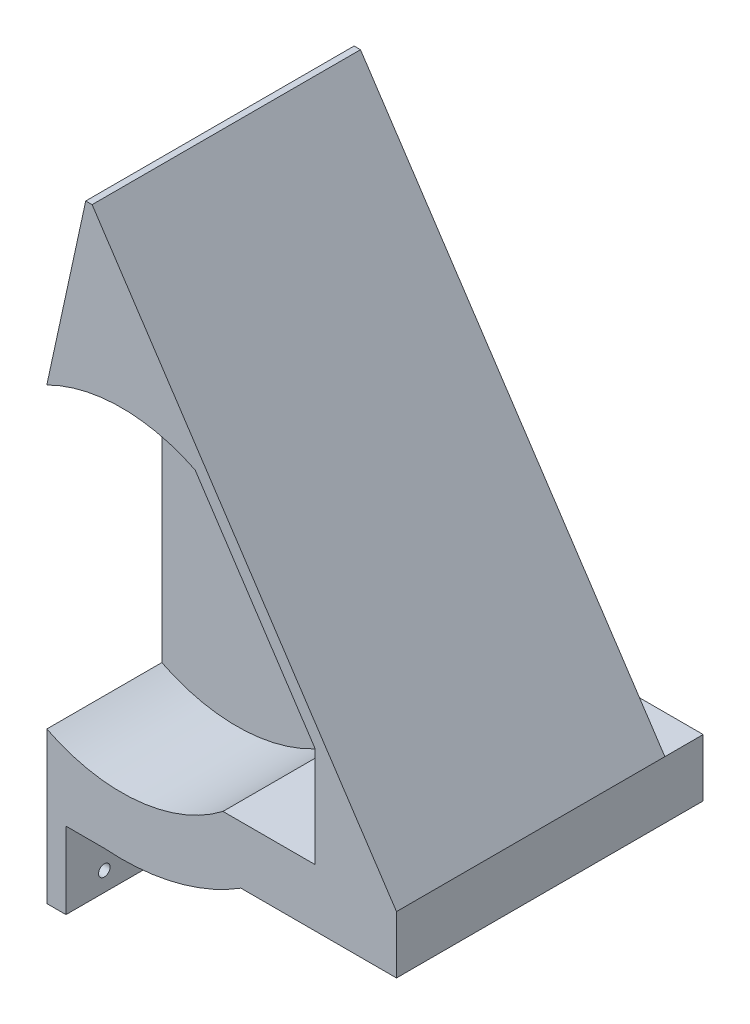
SolidWorks part; units mm, degrees
ref_plane "前视基准面" through (0, 0, 0) normal (0, 0, 1) x (1, 0, 0)
ref_plane "上视基准面" through (0, 0, 0) normal (0, 1, 0) x (1, 0, 0)
ref_plane "右视基准面" through (0, 0, 0) normal (1, 0, 0) x (0, 0, -1)
sketch "草图1" plane through (0, 0, 0) normal (1, 0, 0) x (0, 0, -1)
  line L0 (135, 0) -> (135, -170) construction
  line L1 (0, 0) -> (270, 0)
  line L2 (0, 0) -> (0, -100.2828)
  line L4 (270, 0) -> (270, -100.2828)
  line L5 (38.49, -136.6392) -> (62.3511, -70.3586) construction
  line L6 (21.17, -130.404) -> (127.5448, -168.6989) construction
  line L7 (142.4552, -168.6989) -> (248.83, -130.404) construction
  line L8 (58.2053, -81.8746) -> (-5.8219, -81.8746) construction
  line L9 (58.2053, -81.8746) -> (5.8219, -118.6911) construction
  line L10 (127.5448, -168.6989) -> (21.17, -130.404)
  line L11 (142.4552, -168.6989) -> (248.83, -130.404)
  line L12 (105.5031, -160.7639) -> (135, -78.8281) construction
  line L13 (135, -78.8281) -> (164.4969, -160.7639) construction
  arc A0 (0, -100.2828) -> (21.17, -130.404) centre (32.0136, -100.2828) ccw
  arc A1 (127.5448, -168.6989) -> (142.4552, -168.6989) centre (135, -147.9899) ccw
  arc A2 (270, -100.2828) -> (248.83, -130.404) centre (237.9864, -100.2828) cw
  dimension "D2" = 44.0202
  dimension "D3" = 170
  dimension "D1" = 270
  dimension "D4" = 32.0136
  dimension "D5" = 109.799
  dimension "D6" = 109.799
extrude "凸台-拉伸1" add sketch "草图1" along normal blind 30
sketch "草图2" plane through (30, 0, 0) normal (1, 0, 0) x (0, 0, -1)
  line L0 (135, 0) -> (135, -170) construction
  line L1 (270, 0) -> (0, 0) construction
  line L2 (135, -14.9009) -> (165, -14.9009) construction
  line L3 (165, 0) -> (165, -160.5828)
  line L4 (105, 0) -> (105, -160.5828)
  line L8 (0, 0) -> (0, -100.2828)
  line L9 (21.17, -130.404) -> (127.5448, -168.6989)
  line L10 (142.4552, -168.6989) -> (248.83, -130.404)
  line L11 (270, -100.2828) -> (270, 0)
  line L12 (270, 0) -> (0, 0)
  line L13 (0, 0) -> (0, -100.2828)
  line L14 (21.17, -130.404) -> (127.5448, -168.6989)
  line L15 (142.4552, -168.6989) -> (248.83, -130.404)
  line L16 (270, -100.2828) -> (270, 0)
  line L17 (270, 0) -> (0, 0)
  arc A0 (127.5448, -168.6989) -> (142.4552, -168.6989) centre (135, -147.9899) ccw construction
  arc A4 (0, -100.2828) -> (21.17, -130.404) centre (32.0136, -100.2828) ccw
  arc A5 (127.5448, -168.6989) -> (142.4552, -168.6989) centre (135, -147.9899) ccw
  arc A6 (248.83, -130.404) -> (270, -100.2828) centre (237.9864, -100.2828) ccw
  arc A7 (0, -100.2828) -> (21.17, -130.404) centre (32.0136, -100.2828) ccw
  arc A8 (127.5448, -168.6989) -> (142.4552, -168.6989) centre (135, -147.9899) ccw
  arc A9 (248.83, -130.404) -> (270, -100.2828) centre (237.9864, -100.2828) ccw
  line M12 (0, 0) -> (0, -100.2828)
  arc M13 (0, -100.2828) -> (21.17, -130.404) centre (32.0136, -100.2828) ccw
  line M14 (21.17, -130.404) -> (127.5448, -168.6989)
  line M16 (142.4552, -168.6989) -> (248.83, -130.404)
  arc M17 (248.83, -130.404) -> (270, -100.2828) centre (237.9864, -100.2828) ccw
  line M18 (270, -100.2828) -> (270, 0)
  line M19 (270, 0) -> (0, 0)
  dimension "D1" = 30
  dimension "D2" = 0
extrude "凸台-拉伸2" add sketch "草图2" along normal blind 210 contours L4 M19 M12 M13 M14 | L3 M19 M16 M17 M18
sketch "草图6" plane through (0, 0, -105) normal (0, 0, -1) x (-1, 0, 0)
  line L0 (-71.1167, 0) -> (-71.1167, -409.9146) construction
  line L8 (-30, -160.5828) -> (-30, 0)
  line L9 (-30, 0) -> (-240, 0)
  line L12 (-240, 0) -> (-240, -160.5828)
  line L13 (-240, -160.5828) -> (-30, -160.5828)
  line L15 (-30, -160.5828) -> (-30, 0)
  line L16 (-30, 0) -> (-240, 0)
  line L19 (-240, 0) -> (-240, -160.5828)
  line L20 (-240, -160.5828) -> (-30, -160.5828)
  dimension "D2" = 41.1167
  dimension "D1" = 0
sketch "草图8" plane through (240, 0, 0) normal (1, 0, 0) x (0, 0, -1)
  line L0 (105, 0) -> (105, -160.5828) construction
  line L1 (105, -60) -> (80, -60)
  line L2 (105, -60) -> (105, 60)
  line L3 (105, 60) -> (80, 60)
  line L4 (80, -60) -> (80, 60)
  line L5 (105, -60) -> (80, 60) construction
  line L6 (105, 60) -> (80, -60) construction
  line L7 (135, 0) -> (135, -208.0575) construction
  line L8 (165, 0) -> (105, 0) construction
  line L9 (105, 0) -> (0, 0) construction
  line L10 (165, 60) -> (190, -60) construction
  line L11 (165, -60) -> (190, 60) construction
  line L12 (190, -60) -> (190, 60)
  line L13 (165, 60) -> (190, 60)
  line L14 (165, -60) -> (165, 60)
  line L15 (165, -60) -> (190, -60)
  point P4 (92.5, 0)
  point P17 (177.5, 0)
  dimension "D1" = 25
  dimension "D2" = 60
  dimension "D3" = 60
extrude "凸台-拉伸5" add sketch "草图8" along normal blind 70
sketch "草图9" plane through (240, 0, 0) normal (-1, 0, 0) x (0, 0, 1)
  line L4 (-105, 60) -> (-105, 0)
  line L5 (-105, 0) -> (-80, 0)
  line L6 (-80, 0) -> (-80, 60)
  line L7 (-80, 60) -> (-105, 60)
  line L8 (-105, 60) -> (-105, 0)
  line L9 (-105, 0) -> (-80, 0)
  line L10 (-80, 0) -> (-80, 60)
  line L11 (-80, 60) -> (-105, 60)
  line L12 (-190, 0) -> (-165, 0)
  line L13 (-165, 0) -> (-165, 60)
  line L14 (-165, 60) -> (-190, 60)
  line L15 (-190, 60) -> (-190, 0)
  line L16 (-190, 0) -> (-165, 0)
  line L17 (-165, 0) -> (-165, 60)
  line L18 (-165, 60) -> (-190, 60)
  line L19 (-190, 60) -> (-190, 0)
  dimension "D1" = 0
  dimension "D2" = 0
extrude "凸台-拉伸6" add sketch "草图9" along normal blind 60
sketch "草图10" plane through (0, 0, -80) normal (0, 0, 1) x (1, 0, 0)
  line L0 (240, 0) -> (240, 31.0013) construction
  line L2 (180, 30) -> (270, 30) construction
  line L3 (180, 0) -> (180, 60) construction
  circle A0 centre (270, 30) radius 7.5
  dimension "D2" = 15
  dimension "D1" = 30
extrude "切除-拉伸3" cut sketch "草图10" against normal through all
sketch "草图11" plane through (0, 0, -105) normal (0, 0, -1) x (-1, 0, 0)
  line L0 (0, 0) -> (0, 80.2418) construction
  line L1 (-240, -160.5828) -> (-124.1295, -160.5828) construction
  line L2 (-124.1295, -160.5828) -> (-108.2032, -160.5828) construction
  line L3 (-30, 0) -> (-30, -40) construction
  line L4 (-30, -40) -> (-30, -160.5828)
  line L5 (-30, -160.5828) -> (-108.2032, -160.5828)
  circle A0 centre (-270, 30) radius 240 construction
  arc A1 (-108.2032, -160.5828) -> (-30, -40) centre (-270, 30) ccw
  circle A2 centre (-270, 30) radius 250 construction
  dimension "D1" = 480
  dimension "D2" = 10
extrude "凸台-拉伸7" add sketch "草图11" along normal blind 60
sketch "草图12" plane through (0, 0, -165) normal (0, 0, 1) x (1, 0, 0)
  line L0 (30, 0) -> (240, 0) construction
  line L1 (70, -45) -> (70, 0) construction
  line L4 (30, -160.5828) -> (30, 0) construction
  circle A0 centre (70, -45) radius 2.5
  dimension "D3" = 5
  dimension "D4" = 45
  dimension "D1" = 45
  dimension "D2" = 40
extrude "凸台-拉伸8" add sketch "草图12" along normal through all
sketch "草图13" plane through (0, 0, 0) normal (0, 1, 0) x (1, 0, 0)
  line L0 (0, 270) -> (0, 240.5719) construction
  line L1 (0, 270) -> (0, 0) construction
  line L2 (0, 240.5719) -> (0, 192.1942) construction
sketch "草图14" plane through (0, 0, 0) normal (0, 1, 0) x (1, 0, 0)
  line L0 (0, 250) -> (0, 200)
  line L1 (0, 250) -> (125, 250)
  line L2 (0, 200) -> (125, 200)
  line L3 (125, 250) -> (125, 200)
  line L4 (0, 270) -> (0, 0) construction
  line L5 (240, 270) -> (0, 270) construction
  line L6 (0, 135) -> (52.375, 135) construction
  line L7 (125, 20) -> (125, 70)
  line L8 (0, 70) -> (125, 70)
  line L9 (0, 20) -> (125, 20)
  line L10 (0, 20) -> (0, 70)
  dimension "D1" = 20
  dimension "D2" = 50
  dimension "D3" = 125
extrude "凸台-拉伸9" add sketch "草图14" along normal blind 120
sketch "草图15" plane through (0, 0, -20) normal (0, 0, 1) x (1, 0, 0)
  line L0 (0, 120) -> (0, 0) construction
  line L1 (0, 70) -> (70, 70)
  line L2 (0, 70) -> (0, 0)
  line L3 (0, 0) -> (70, 0)
  line L4 (70, 70) -> (70, 0)
  line L5 (0, 120) -> (125, 120) construction
  dimension "D1" = 70
  dimension "D2" = 70
  dimension "D3" = 50
extrude "切除-拉伸4" cut sketch "草图15" against normal blind 10
sketch "草图16" plane through (0, 0, -30) normal (0, 0, 1) x (1, 0, 0)
  line L0 (0, 35) -> (70, 35) construction
  line L1 (0, 70) -> (0, 0) construction
  line L2 (70, 0) -> (70, 70) construction
  line L3 (0, 35) -> (35, 35) construction
  line L4 (35, 70) -> (35, 0) construction
  line L5 (35, 35) -> (35, 15)
  line L6 (70, 70) -> (0, 70) construction
  line L7 (0, 35) -> (35, 35) construction
  line L8 (0, 0) -> (70, 0) construction
  line L9 (35, 35) -> (35, 55) construction
  line L10 (35, 55) -> (5, 55) construction
  line L11 (35, 35) -> (35, 55)
  line L12 (35, 55) -> (5, 55)
  line L13 (5, 55) -> (5, 15)
  line L14 (35, 15) -> (5, 15)
  point P21 (5, 35)
  dimension "D1" = 35
  dimension "D2" = 20
  dimension "D3" = 30
extrude "切除-拉伸5" cut sketch "草图16" against normal blind 20 contours L14 L5 L11 L12 L13
sketch "草图17" plane through (0, 0, -30) normal (0, 0, 1) x (1, 0, 0)
  line L0 (35, 35) -> (19.5, 34.5) construction
  line L1 (35, 55) -> (35, 15) construction
  circle A0 centre (19.5, 34.5) radius 43.4713
extrude "切除-拉伸6" cut sketch "草图17" along normal through all
sketch "草图18" plane through (0, 0, -20) normal (0, 0, 1) x (1, 0, 0)
  line L0 (0, 73.3523) -> (11.8199, 120) construction
  line L1 (0, 73.3523) -> (0, -4.3523) construction
  line L2 (0, 120) -> (125, 120) construction
  line L3 (11.8199, 120) -> (62.5, 43.3973) construction
  line L4 (62.5, 43.3973) -> (91.2115, 0) construction
  line L5 (11.8199, 120) -> (91.2115, 0)
  line L6 (91.2115, 0) -> (87.3179, 0)
  line L7 (70, 0) -> (125, 0) construction
  line L8 (87.3179, 0) -> (10.7417, 115.7446)
  line L9 (10.7417, 115.7446) -> (11.8199, 120)
  arc A0 (44.5899, 70) -> (0, 73.3523) centre (19.5, 34.5) ccw construction
extrude "凸台-拉伸10" add sketch "草图18" along normal blind 20
sketch "草图19" plane through (0, 0, -20) normal (0, 0, 1) x (1, 0, 0)
  line L0 (10.856, 115.5717) -> (11.8199, 120)
  line L1 (10.7417, 115.7446) -> (87.3179, 0) construction
  line L2 (11.8199, 120) -> (10.7417, 115.7446) construction
  line L3 (11.8199, 120) -> (125, 120) construction
  line L4 (11.8199, 120) -> (0, 65.6972)
  line L5 (0, 73.3523) -> (0, -4.3523) construction
  line L6 (0, 65.6972) -> (0, 73.3523)
  line L7 (0, 120) -> (0, 73.3523) construction
  line L8 (0, 73.3523) -> (10.1537, 120)
  line L9 (0, 120) -> (11.8199, 120) construction
  line L10 (10.1537, 120) -> (11.8199, 120)
  line L11 (10.1537, 120) -> (11.8199, 120)
  line M2 (38.6846, 73.509) -> (10.7417, 115.7446)
  line M3 (10.7417, 115.7446) -> (11.8199, 120)
  line M4 (11.8199, 120) -> (0, 120)
  arc M6 (0, 73.3523) -> (38.6846, 73.509) centre (19.5, 34.5) cw
extrude "凸台-拉伸11" add sketch "草图19" along normal blind 20 contours L8 L4 M6 M2 M3 M4
sketch "草图20" plane through (0, 0, -20) normal (0, 0, 1) x (1, 0, 0)
  line L3 (0, 120) -> (0, 73.3523)
  line L4 (0, 73.3523) -> (10.1537, 120)
  line L5 (10.1537, 120) -> (0, 120)
  line L6 (0, 120) -> (0, 73.3523)
  line L7 (0, 73.3523) -> (10.1537, 120)
  line L8 (10.1537, 120) -> (0, 120)
  dimension "D1" = 0
extrude "切除-拉伸7" cut sketch "草图20" against normal through all
sketch "草图22" plane through (0, 0, -20) normal (0, 0, 1) x (1, 0, 0)
  line L0 (44.8997, 70) -> (70, 32.0611)
  line L7 (70, 32.0611) -> (91.2115, 0)
  line L8 (91.2115, 0) -> (125, 0)
  line L9 (125, 0) -> (125, 120)
  line L10 (125, 120) -> (11.8199, 120)
  line L11 (11.8199, 120) -> (44.8997, 70)
  line L12 (44.8997, 70) -> (70, 70)
  line L13 (70, 70) -> (70, 32.0611)
  line L14 (70, 32.0611) -> (91.2115, 0)
  line L15 (91.2115, 0) -> (125, 0)
  line L16 (125, 0) -> (125, 120)
  line L17 (125, 120) -> (11.8199, 120)
  line L18 (11.8199, 120) -> (44.8997, 70)
  dimension "D1" = 0
extrude "切除-拉伸8" cut sketch "草图22" against normal through all
sketch "草图23" plane through (0, 0, 0) normal (0, 0, 1) x (1, 0, 0)
  line L0 (87.3179, 0) -> (91.2115, 0)
  line L10 (0, -4.3523) -> (0, -100.2828)
  line L11 (0, -100.2828) -> (240, -100.2828)
  line L12 (240, -100.2828) -> (240, 0)
  line L13 (240, 0) -> (91.2115, 0)
  line L14 (91.2115, 0) -> (11.8199, 120)
  line L15 (11.8199, 120) -> (10.1537, 120)
  line L16 (10.1537, 120) -> (0, 73.3523)
  line L17 (1.8573, 74.2302) -> (10.856, 115.5717)
  line L18 (10.856, 115.5717) -> (87.3179, 0)
  line L19 (87.3179, 0) -> (45.9481, 0)
  line L20 (0, -4.3523) -> (0, -100.2828)
  line L21 (0, -100.2828) -> (240, -100.2828)
  line L22 (240, -100.2828) -> (240, 0)
  line L23 (240, 0) -> (91.2115, 0)
  line L24 (91.2115, 0) -> (11.8199, 120)
  line L25 (11.8199, 120) -> (10.1537, 120)
  line L26 (10.1537, 120) -> (0, 73.3523)
  line L27 (1.8573, 74.2302) -> (10.856, 115.5717)
  line L28 (10.856, 115.5717) -> (87.3179, 0)
  line L29 (87.3179, 0) -> (45.9481, 0)
  arc A2 (0, -4.3523) -> (45.9481, 0) centre (19.5, 34.5) ccw
  arc A3 (1.8573, 74.2302) -> (0, 73.3523) centre (19.5, 34.5) ccw
  arc A4 (0, -4.3523) -> (45.9481, 0) centre (19.5, 34.5) ccw
  arc A5 (1.8573, 74.2302) -> (0, 73.3523) centre (19.5, 34.5) ccw
  line M18 (91.2115, 0) -> (11.8199, 120)
  line M19 (11.8199, 120) -> (10.1537, 120)
  line M20 (10.1537, 120) -> (0, 73.3523)
  arc M21 (0, 73.3523) -> (1.8573, 74.2302) centre (19.5, 34.5) cw
  line M22 (1.8573, 74.2302) -> (10.856, 115.5717)
  line M23 (10.856, 115.5717) -> (87.3179, 0)
  dimension "D1" = 0
extrude "凸台-拉伸19" add sketch "草图23" against normal up to next contours L0 M23 M18 M19 M20 M21 M22
sketch "草图24" plane through (0, 0, -20) normal (0, 0, 1) x (1, 0, 0)
  line L3 (87.3179, 0) -> (70, 26.1759)
  line L4 (70, 26.1759) -> (70, 0)
  line L5 (70, 0) -> (87.3179, 0)
  line L6 (87.3179, 0) -> (70, 26.1759)
  line L7 (70, 26.1759) -> (70, 0)
  line L8 (70, 0) -> (87.3179, 0)
  dimension "D1" = 0
extrude "凸台-拉伸20" add sketch "草图24" along normal up to vertex (20 mm away)
sketch "草图25" plane through (0, 0, -20) normal (0, 0, 1) x (1, 0, 0)
  line L2 (38.6846, 73.509) -> (10.856, 115.5717)
  line L3 (10.856, 115.5717) -> (1.8573, 74.2302)
  line L4 (38.6846, 73.509) -> (10.856, 115.5717)
  line L5 (10.856, 115.5717) -> (1.8573, 74.2302)
  arc A1 (38.6846, 73.509) -> (1.8573, 74.2302) centre (19.5, 34.5) ccw
  arc A2 (38.6846, 73.509) -> (1.8573, 74.2302) centre (19.5, 34.5) ccw
  dimension "D1" = 0
extrude "凸台-拉伸21" add sketch "草图25" along normal blind 20
sketch "草图26" plane through (0, 0, -250) normal (0, 0, -1) x (-1, 0, 0)
  line L10 (-70, 26.1759) -> (-38.6846, 73.509)
  line L11 (-70, 0) -> (-70, 26.1759)
  line L12 (-45.9481, 0) -> (-70, 0)
  line L13 (0, -100.2828) -> (0, -4.3523)
  line L14 (-240, -100.2828) -> (0, -100.2828)
  line L15 (-240, 0) -> (-240, -100.2828)
  line L16 (-91.2115, 0) -> (-240, 0)
  line L17 (-11.8199, 120) -> (-91.2115, 0)
  line L18 (-10.1537, 120) -> (-11.8199, 120)
  line L19 (0, 73.3523) -> (-10.1537, 120)
  line L20 (-70, 26.1759) -> (-38.6846, 73.509)
  line L21 (-70, 0) -> (-70, 26.1759)
  line L22 (-45.9481, 0) -> (-70, 0)
  line L23 (0, -100.2828) -> (0, -4.3523)
  line L24 (-240, -100.2828) -> (0, -100.2828)
  line L25 (-240, 0) -> (-240, -100.2828)
  line L26 (-91.2115, 0) -> (-240, 0)
  line L27 (-11.8199, 120) -> (-91.2115, 0)
  line L28 (-10.1537, 120) -> (-11.8199, 120)
  line L29 (0, 73.3523) -> (-10.1537, 120)
  arc A2 (0, 73.3523) -> (-38.6846, 73.509) centre (-19.5, 34.5) ccw
  arc A3 (-45.9481, 0) -> (0, -4.3523) centre (-19.5, 34.5) ccw
  arc A4 (0, 73.3523) -> (-38.6846, 73.509) centre (-19.5, 34.5) ccw
  arc A5 (-45.9481, 0) -> (0, -4.3523) centre (-19.5, 34.5) ccw
  dimension "D1" = 0
extrude "凸台-拉伸22" add sketch "草图26" along normal blind 20
sketch "草图27" plane through (0, 0, -270) normal (0, 0, -1) x (-1, 0, 0)
  line L4 (-38.6846, 73.509) -> (-70, 26.1759)
  line L5 (0, -4.3523) -> (0, 73.3523)
  line L6 (-70, 0) -> (-45.9481, 0)
  line L7 (-70, 26.1759) -> (-70, 0)
  line L8 (-38.6846, 73.509) -> (-70, 26.1759)
  line L9 (0, -4.3523) -> (0, 73.3523)
  line L10 (-70, 0) -> (-45.9481, 0)
  line L11 (-70, 26.1759) -> (-70, 0)
  arc A2 (0, 73.3523) -> (-38.6846, 73.509) centre (-19.5, 34.5) ccw
  arc A3 (-45.9481, 0) -> (0, -4.3523) centre (-19.5, 34.5) ccw
  arc A4 (0, 73.3523) -> (-38.6846, 73.509) centre (-19.5, 34.5) ccw
  arc A5 (-45.9481, 0) -> (0, -4.3523) centre (-19.5, 34.5) ccw
  dimension "D1" = 0
extrude "切除-拉伸9" cut sketch "草图27" against normal blind 30
sketch "草图29" plane through (0, 0, -70) normal (0, 0, -1) x (-1, 0, 0)
  line L0 (-5, 55) -> (-35, 15) construction
  line L1 (-5, 15) -> (-35, 55) construction
  line L4 (-35, 15) -> (-5, 15)
  line L5 (-35, 55) -> (-35, 15)
  line L6 (-5, 55) -> (-35, 55)
  line L7 (-5, 15) -> (-5, 55)
  line L8 (-35, 15) -> (-5, 15) construction
  line L9 (-35, 55) -> (-35, 15) construction
  line L10 (-5, 55) -> (-35, 55) construction
  line L11 (-5, 15) -> (-5, 55) construction
  circle A0 centre (-20, 35) radius 15
  dimension "D2" = 30
  dimension "D1" = 0
extrude "切除-拉伸11" cut sketch "草图29" against normal through all both and the other way through all
sketch "草图30" plane through (30, 0, 0) normal (1, 0, 0) x (0, 0, -1)
  line L3 (142.4552, -168.6989) -> (165, -160.5828)
  line L4 (165, -160.5828) -> (105, -160.5828)
  line L5 (105, -160.5828) -> (127.5448, -168.6989)
  line L6 (142.4552, -168.6989) -> (165, -160.5828)
  line L7 (165, -160.5828) -> (105, -160.5828)
  line L8 (105, -160.5828) -> (127.5448, -168.6989)
  arc A1 (127.5448, -168.6989) -> (142.4552, -168.6989) centre (135, -147.9899) ccw
  arc A2 (127.5448, -168.6989) -> (142.4552, -168.6989) centre (135, -147.9899) ccw
  dimension "D1" = 0
extrude "凸台-拉伸23" add sketch "草图30" along normal up to vertex (78.2032 mm away)
sketch "草图33" plane through (0, 0, -240) normal (0, 0, -1) x (-1, 0, 0)
  line L0 (-35, 15) -> (-5, 15) construction
  line L1 (-35, 55) -> (-35, 15) construction
  line L2 (-35, 55) -> (-5, 55) construction
  line L3 (-5, 55) -> (-5, 15) construction
  line L4 (-35, 15) -> (-5, 15)
  line L5 (-35, 55) -> (-35, 15)
  line L6 (-35, 55) -> (-5, 55)
  line L7 (-5, 55) -> (-5, 15)
extrude "切除-拉伸14" cut sketch "草图33" against normal blind 20
sketch "草图34" plane through (0, 0, -200) normal (0, 0, 1) x (1, 0, 0)
  line L0 (20, 50) -> (20, 2.4606) construction
  line L1 (11, 0) -> (11, 35.3006)
  line L2 (11, 0) -> (29, 0)
  line L3 (11, 35.3006) -> (29, 35.3006)
  line L4 (29, 0) -> (29, 35.3006)
  line L5 (11, 0) -> (29, 35.3006) construction
  line L6 (11, 35.3006) -> (29, 0) construction
  line L7 (0, 0) -> (91.2115, 0) construction
  arc A0 (35, 35) -> (5, 35) centre (20, 35) ccw construction
  point P7 (20, 17.6503)
  dimension "D1" = 18
extrude "切除-拉伸15" cut sketch "草图34" against normal blind 10
sketch "草图35" plane through (0, 0, -70) normal (0, 0, -1) x (-1, 0, 0)
  line L3 (-11, 0) -> (-11, 23)
  line L4 (-29, 0) -> (-11, 0)
  line L5 (-29, 23) -> (-29, 0)
  line L6 (-11, 0) -> (-11, 23)
  line L7 (-29, 0) -> (-11, 0)
  line L8 (-29, 23) -> (-29, 0)
  arc A1 (-29, 23) -> (-11, 23) centre (-20, 35) ccw
  arc A2 (-29, 23) -> (-11, 23) centre (-20, 35) ccw
  dimension "D1" = 0
extrude "切除-拉伸16" cut sketch "草图35" against normal blind 10
sketch "草图36" plane through (0, 0, 0) normal (-1, 0, 0) x (0, 0, 1)
  line L0 (-235.6917, -100.008) -> (-211.6417, -100.008) construction
  line L1 (-135, -147.9899) -> (-135, -104.794) construction
  line L2 (-34.3083, -100.008) -> (-58.3583, -100.008) construction
  circle A0 centre (-235.6917, -100.008) radius 15.9
  circle A1 centre (-34.3083, -100.008) radius 15.9
  ellipse E0 centre (-235.6917, -100.008) end of major axis (-211.6417, -100.008) minor radius 15.9
  ellipse E1 centre (-34.3083, -100.008) end of major axis (-58.3583, -100.008) minor radius 15.9
  dimension "D2" = 31.8
  dimension "D1" = 24.05
extrude "切除-拉伸17" cut sketch "草图36" against normal blind 4 contours A0 E0 | A0 | A0 E0 | E1 A1 | A1 | E1 A1
sketch "草图37" plane through (0, 0, 0) normal (0, 1, 0) x (1, 0, 0)
  line L0 (108.2032, 135) -> (337.5794, 135) construction
  line L1 (240, 80) -> (91.2115, 80)
  line L2 (240, 80) -> (240, 0)
  line L3 (240, 0) -> (91.2115, 0)
  line L4 (91.2115, 80) -> (91.2115, 0)
  line L5 (108.2032, 165) -> (108.2032, 105) construction
  line L6 (91.2115, 190) -> (91.2115, 270)
  line L7 (240, 270) -> (91.2115, 270)
  line L8 (240, 190) -> (240, 270)
  line L9 (240, 190) -> (91.2115, 190)
extrude "切除-拉伸18" cut sketch "草图37" against normal through all
sketch "草图38" plane through (0, 0, 0) normal (0, 0, 1) x (1, 0, 0)
  line L1 (70, -15) -> (76.2115, -15)
  line L2 (76.2115, -85.2828) -> (76.2115, -15)
  line L3 (15, -85.2828) -> (76.2115, -85.2828)
  line L4 (15, -23.7978) -> (15, -85.2828)
  line L5 (70, -15) -> (50.623, -15)
  line L6 (76.2115, -15) -> (91.2115, -15)
  line L7 (91.2115, -100.2828) -> (91.2115, 0) construction
  line L8 (91.2115, -15) -> (91.2115, -100.2828)
  line L9 (91.2115, -100.2828) -> (0, -100.2828) construction
  line L10 (91.2115, -100.2828) -> (15, -100.2828)
  line L11 (15, -100.2828) -> (15, -85.2828)
  line L12 (91.2115, -15) -> (91.2115, -100.2828)
  line L14 (91.2115, -151.5828) -> (91.2115, 0) construction
  line L15 (91.2115, -151.5828) -> (91.2115, 0)
  line L17 (91.2115, -151.5828) -> (15, -151.5828)
  line L18 (91.2115, -151.5828) -> (91.2115, -100.2828)
  line L19 (91.2115, -100.2828) -> (15, -100.2828)
  line L20 (15, -151.5828) -> (15, -100.2828)
  arc A0 (15, -23.7978) -> (50.623, -15) centre (19.5, 34.5) ccw
  line M12 (0, -100.2828) -> (91.2115, -100.2828)
  line M13 (91.2115, -100.2828) -> (91.2115, 0)
extrude "切除-拉伸20" cut sketch "草图38" against normal blind 80 contours L20 L17 L15 M12 | L11 L6 L2 L3 M12 M13 | A0 L4 L3 L2 L1 L5
sketch "草图39" plane through (0, 0, -270) normal (0, 0, -1) x (-1, 0, 0)
  line L10 (-180, 60) -> (-310, 60)
  line L11 (-180, 0) -> (-180, 60)
  line L12 (-91.2115, 0) -> (-180, 0)
  line L13 (-91.2115, -15) -> (-91.2115, 0)
  line L14 (-50.623, -15) -> (-91.2115, -15)
  line L15 (-15, -151.5828) -> (-15, -23.7978)
  line L16 (-240, -151.5828) -> (-15, -151.5828)
  line L17 (-240, -60) -> (-240, -151.5828)
  line L18 (-310, -60) -> (-240, -60)
  line L19 (-310, 60) -> (-310, -60)
  line L20 (-180, 60) -> (-310, 60)
  line L21 (-180, 0) -> (-180, 60)
  line L22 (-91.2115, 0) -> (-180, 0)
  line L23 (-91.2115, -15) -> (-91.2115, 0)
  line L24 (-50.623, -15) -> (-91.2115, -15)
  line L25 (-15, -151.5828) -> (-15, -23.7978)
  line L26 (-240, -151.5828) -> (-15, -151.5828)
  line L27 (-240, -60) -> (-240, -151.5828)
  line L28 (-310, -60) -> (-240, -60)
  line L29 (-310, 60) -> (-310, -60)
  arc A1 (-50.623, -15) -> (-15, -23.7978) centre (-19.5, 34.5) ccw
  arc A2 (-50.623, -15) -> (-15, -23.7978) centre (-19.5, 34.5) ccw
  dimension "D1" = 0
extrude "切除-拉伸21" cut sketch "草图39" against normal blind 81
sketch "草图40" plane through (0, 0, -80) normal (0, 0, 1) x (1, 0, 0)
  line L0 (98.1638, -151.5828) -> (30, -151.5828) construction
  line L1 (240, -151.5828) -> (15, -151.5828) construction
  line L2 (30, -151.5828) -> (30, -40) construction
  line L3 (74.6558, -141.5828) -> (40, -141.5828)
  line L4 (40, -141.5828) -> (40, -91.2436)
  arc A1 (30, -40) -> (108.2032, -160.5828) centre (270, 30) ccw construction
  arc A2 (30, -40) -> (98.1638, -151.5828) centre (270, 30) ccw construction
  arc A3 (40, -91.2436) -> (74.6558, -141.5828) centre (270, 30) ccw
  dimension "D1" = 10
extrude "切除-拉伸22" cut sketch "草图40" against normal through all
sketch "草图41" plane through (0, 0, 0) normal (0, 1, 0) x (1, 0, 0)
  line L0 (29, 60) -> (11, 60) construction
  line L1 (29, 60) -> (11, 60)
  line L2 (29, 60) -> (29, 70) construction
  line L3 (29, 60) -> (29, 70)
  line L4 (11, 60) -> (11, 70) construction
  line L5 (11, 60) -> (11, 70)
  line L6 (11, 70) -> (29, 70)
  line L7 (0, 135) -> (128.1299, 135) construction
  line L8 (0, 200) -> (0, 70) construction
  line L9 (11, 200) -> (29, 200)
  line L10 (11, 210) -> (11, 200)
  line L11 (29, 210) -> (29, 200)
  line L12 (29, 210) -> (11, 210)
extrude "切除-拉伸23" cut sketch "草图41" against normal blind 60
sketch "草图44" plane through (0, 60, 0) normal (0, 1, 0) x (1, 0, 0)
  line L0 (310, 80) -> (180, 80) construction
  line L1 (310, 189) -> (260, 189)
  line L2 (310, 189) -> (310, 80)
  line L3 (310, 80) -> (260, 80)
  line L4 (260, 189) -> (260, 80)
  dimension "D1" = 50
extrude "凸台-拉伸26" add sketch "草图44" along normal blind 15
sketch "草图45" plane through (0, -60, 0) normal (0, -1, 0) x (1, 0, 0)
  line L0 (310, -189) -> (240, -189) construction
  line L1 (310, -80) -> (260, -80)
  line L2 (310, -80) -> (310, -189)
  line L3 (310, -189) -> (260, -189)
  line L4 (260, -80) -> (260, -189)
  dimension "D1" = 50
extrude "凸台-拉伸27" add sketch "草图45" along normal blind 15
sketch "草图46" plane through (240, 0, 0) normal (1, 0, 0) x (0, 0, -1)
  line L0 (80, -151.5828) -> (105, -160.5828) construction
  line L1 (80, -151.5828) -> (105, -160.5828)
  line L2 (165, -160.5828) -> (190, -151.5828) construction
  line L3 (165, -160.5828) -> (189, -151.9428)
  line L4 (105, -160.5828) -> (165, -160.5828)
  line L5 (189, -60) -> (189, -151.5828) construction
  line L7 (80, -151.5828) -> (80, -130.5828)
  line L8 (80, -130.5828) -> (189, -130.5828)
  line L10 (189, -130.5828) -> (189, -151.9428)
  dimension "D2" = 30
extrude "凸台-拉伸28" add sketch "草图46" along normal blind 15
sketch "草图47" plane through (0, 0, -189) normal (0, 0, -1) x (-1, 0, 0)
  line L1 (-40, -91.2436) -> (-25, -91.2436)
  line L2 (-40, -91.2436) -> (-40, -141.5828)
  line L3 (-40, -141.5828) -> (-25, -141.5828)
  line L4 (-25, -91.2436) -> (-25, -141.5828)
  arc A0 (-74.6558, -141.5828) -> (-40, -91.2436) centre (-270, 30) ccw construction
  arc A1 (-74.6558, -141.5828) -> (-40, -91.2436) centre (-270, 30) ccw construction
  arc A2 (-108.2032, -160.5828) -> (-30, -40) centre (-270, 30) ccw construction
  arc A3 (-108.2032, -160.5828) -> (-30, -40) centre (-270, 30) ccw construction
  dimension "D1" = 15
extrude "切除-拉伸24" cut sketch "草图47" against normal up to surface (109 mm away) up to face at (51.0572, -125.1437, -80)
sketch "草图48" plane through (310, 0, 0) normal (1, 0, 0) x (0, 0, -1)
  line L5 (270, 120) -> (80, 120)
  line L6 (270, 120) -> (270, -151.5828)
  line L8 (80, 120) -> (80, -151.5828)
  line L10 (80, -151.5828) -> (80, -184.4308)
  line L11 (80, -184.4308) -> (270, -184.4308)
  line L12 (270, -151.5828) -> (270, -184.4308)
extrude "切除-拉伸25" cut sketch "草图48" against normal through all
sketch "草图49" plane through (0, 0, 0) normal (-1, 0, 0) x (0, 0, 1)
  line L0 (-70, -23.7978) -> (-60, -23.7978)
  line L8 (-60, -23.7978) -> (-60, -60)
  line L9 (0, -23.7978) -> (-60, -23.7978)
  line L10 (0, -100.2828) -> (0, -23.7978)
  line L11 (-80, -151.5828) -> (-21.17, -130.404)
  line L12 (-80, -23.7978) -> (-80, -151.5828)
  line L13 (-70, -23.7978) -> (-80, -23.7978)
  line L14 (-70, -60) -> (-70, -23.7978)
  line L15 (-60, -60) -> (-70, -60)
  line L17 (0, -23.7978) -> (-60, -23.7978)
  line L18 (0, -100.2828) -> (0, -23.7978)
  line L19 (-80, -151.5828) -> (-21.17, -130.404)
  line L20 (-80, -23.7978) -> (-80, -151.5828)
  line L21 (-70, -23.7978) -> (-80, -23.7978)
  arc A1 (-21.17, -130.404) -> (0, -100.2828) centre (-32.0136, -100.2828) ccw
  arc A2 (-21.17, -130.404) -> (0, -100.2828) centre (-32.0136, -100.2828) ccw
  dimension "D1" = 0
extrude "切除-拉伸26" cut sketch "草图49" against normal blind 15
sketch "草图50" plane through (0, -23.7978, 0) normal (0, -1, 0) x (1, 0, 0)
  line L0 (15, -80) -> (0, -80) construction
  line L1 (0, 0) -> (5, 0)
  line L2 (0, 0) -> (0, -80)
  line L3 (0, -80) -> (5, -80)
  line L4 (5, 0) -> (5, -80)
  dimension "D1" = 5
extrude "凸台-拉伸29" add sketch "草图50" along normal blind 20
sketch "草图51" plane through (5, 0, 0) normal (1, 0, 0) x (0, 0, -1)
  line L0 (80, -33.7978) -> (0, -33.7978) construction
  line L1 (80, -43.7978) -> (80, -23.7978) construction
  line L2 (0, -43.7978) -> (0, -23.7978) construction
  line L3 (70, -33.7978) -> (70, -43.7978) construction
  line L4 (80, -43.7978) -> (0, -43.7978) construction
  line L5 (70, -38.7978) -> (0, -38.7978) construction
  line L6 (40, -43.7978) -> (40, -23.7978) construction
  line L7 (80, -23.7978) -> (0, -23.7978) construction
  circle A1 centre (70, -38.7978) radius 1.5
  circle A2 centre (10, -38.7978) radius 1.5
  dimension "D1" = 3
  dimension "D2" = 10
extrude "切除-拉伸27" cut sketch "草图51" against normal blind 20
sketch "草图52" plane through (0, 0, -30) normal (0, 0, 1) x (1, 0, 0)
  line L3 (35, 35) -> (35, 55)
  line L4 (35, 55) -> (5, 55)
  line L5 (5, 55) -> (5, 35)
  line L6 (35, 35) -> (35, 55)
  line L7 (35, 55) -> (5, 55)
  line L8 (5, 55) -> (5, 35)
  line L9 (5, 35) -> (5, 15)
  line L10 (5, 15) -> (35, 15)
  line L11 (35, 15) -> (35, 35)
  line L12 (5, 35) -> (5, 15)
  line L13 (5, 15) -> (35, 15)
  line L14 (35, 15) -> (35, 35)
  arc A1 (35, 35) -> (5, 35) centre (20, 35) ccw
  arc A3 (5, 35) -> (35, 35) centre (20, 35) ccw
  dimension "D1" = 0
  dimension "D2" = 0
extrude "凸台-拉伸30" add sketch "草图52" against normal up to surface (20 mm away) up to face at (20, 48.75, -50)
sketch "草图53" plane through (0, 0, -70) normal (0, 0, -1) x (-1, 0, 0)
  line L3 (-15, -23.7978) -> (-11, -23.7978)
  line L4 (-11, -23.7978) -> (-11, 23)
  line L5 (-29, 23) -> (-29, -23.1944)
  line L6 (-15, -23.7978) -> (-11, -23.7978)
  line L7 (-11, -23.7978) -> (-11, 23)
  line L8 (-29, 23) -> (-29, -23.1944)
  circle A1 centre (-20, 35) radius 15
  circle A2 centre (-20, 35) radius 15
  arc A4 (-29, 23) -> (-11, 23) centre (-20, 35) ccw
  arc A5 (-29, -23.1944) -> (-15, -23.7978) centre (-19.5, 34.5) ccw
  arc A6 (-29, 23) -> (-11, 23) centre (-20, 35) ccw
  arc A7 (-29, -23.1944) -> (-15, -23.7978) centre (-19.5, 34.5) ccw
  arc M7 (-29, 23) -> (-11, 23) centre (-20, 35) cw
  line M8 (-11, 23) -> (-11, 0)
  line M15 (-29, 0) -> (-29, 23)
  dimension "D1" = 0
  dimension "D2" = 0
extrude "凸台-拉伸31" add sketch "草图53" against normal up to surface (10 mm away) contours A2 M7 | L8 A7 L6 L7 A2 M8 M15 up to face at (19.0036, -5.6422, -60)
sketch "草图54" plane through (0, 0, -80) normal (0, 0, -1) x (-1, 0, 0)
  line L0 (-91.2115, -7.5) -> (0, -7.5) construction
  line L1 (-91.2115, -15) -> (-91.2115, 0) construction
  line L2 (0, 0) -> (0, -43.7978) construction
  line L3 (-91.2115, -7.5) -> (-76.2115, -7.5) construction
  line L4 (0, -7.5) -> (-15, -7.5) construction
  circle A0 centre (-76.2115, -7.5) radius 1.5
  circle A1 centre (-15, -7.5) radius 1.5
  dimension "D3" = 3
  dimension "D4" = 3
  dimension "D1" = 15
  dimension "D2" = 15
extrude "切除-拉伸28" cut sketch "草图54" against normal blind 10
sketch "草图56" plane through (0, 0, -80) normal (0, 0, -1) x (-1, 0, 0)
  line L7 (-15, -23.7978) -> (-5, -23.7978)
  line L8 (-5, -23.7978) -> (-5, -43.7978)
  line L9 (-5, -43.7978) -> (0, -43.7978)
  line L10 (0, -43.7978) -> (0, 0)
  line L11 (0, 0) -> (-91.2115, 0)
  line L12 (-91.2115, 0) -> (-91.2115, -15)
  line L13 (-91.2115, -15) -> (-50.623, -15)
  line L14 (-15, -23.7978) -> (-5, -23.7978)
  line L15 (-5, -23.7978) -> (-5, -43.7978)
  line L16 (-5, -43.7978) -> (0, -43.7978)
  line L17 (0, -43.7978) -> (0, 0)
  line L18 (0, 0) -> (-91.2115, 0)
  line L19 (-91.2115, 0) -> (-91.2115, -15)
  line L20 (-91.2115, -15) -> (-50.623, -15)
  arc A1 (-50.623, -15) -> (-15, -23.7978) centre (-19.5, 34.5) ccw
  arc A2 (-50.623, -15) -> (-15, -23.7978) centre (-19.5, 34.5) ccw
  dimension "D1" = 0
